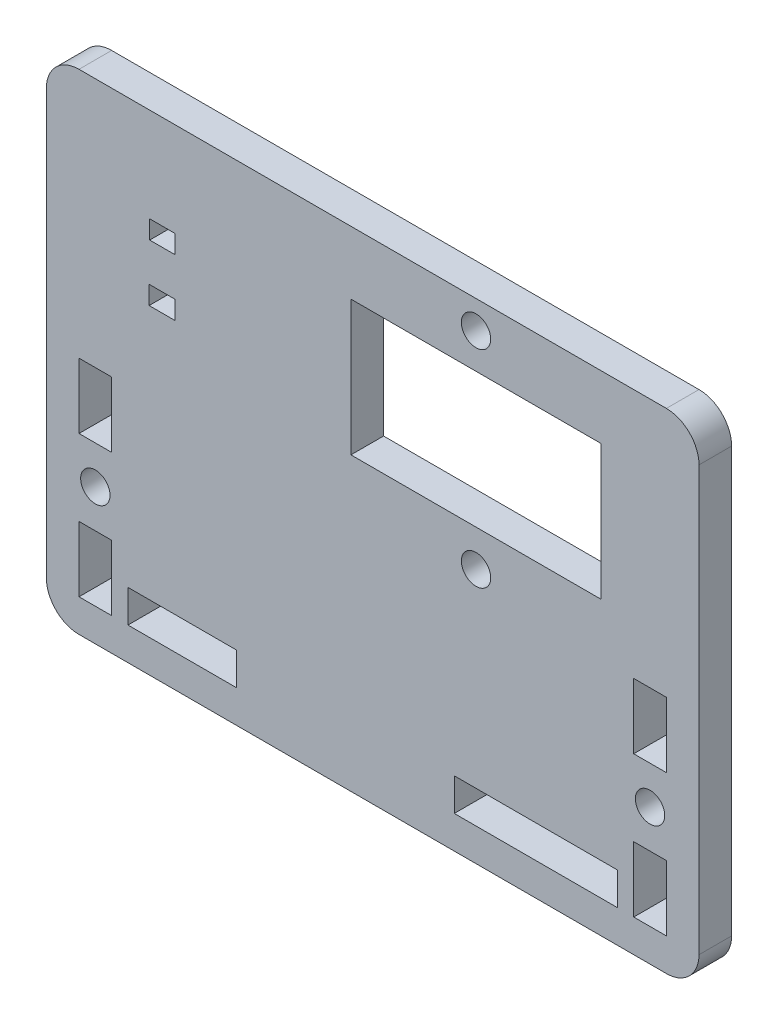
SolidWorks part; units mm, degrees
ref_plane "前视基准面" through (0, 0, 0) normal (0, 0, 1) x (1, 0, 0)
ref_plane "上视基准面" through (0, 0, 0) normal (0, 1, 0) x (1, 0, 0)
ref_plane "右视基准面" through (0, 0, 0) normal (1, 0, 0) x (0, 0, -1)
ref_plane "基准面1" through (0, 0, 0) normal (0, 0, -1) x (-1, 0, 0)
sketch "草图1" plane through (0, 0, 0) normal (0, 0, -1) x (-1, 0, 0)
  line L0 (-28.0668, 21.999) -> (-25.0668, 21.999)
  line L1 (-25.0668, 21.999) -> (-25.0668, 15.999)
  line L2 (-25.0668, 15.999) -> (-28.0668, 15.999)
  line L3 (-28.0668, 15.999) -> (-28.0668, 21.999)
  line L4 (-28.0668, 0) -> (25.9332, 0)
  line L5 (28.9332, 3) -> (28.9332, 41.999)
  line L6 (25.9332, 44.999) -> (-28.0668, 44.999)
  line L7 (-31.0668, 41.999) -> (-31.0668, 3)
  line L8 (-28.0668, 8.999) -> (-25.0668, 8.999)
  line L9 (-25.0668, 8.999) -> (-25.0668, 2.999)
  line L10 (-25.0668, 2.999) -> (-28.0668, 2.999)
  line L11 (-28.0668, 2.999) -> (-28.0668, 8.999)
  line L12 (-23.5678, 5.999) -> (-8.5678, 5.999)
  line L13 (-8.5678, 5.999) -> (-8.5678, 2.999)
  line L14 (-8.5678, 2.999) -> (-23.5678, 2.999)
  line L15 (-23.5678, 2.999) -> (-23.5678, 5.999)
  line L16 (-22.0668, 39.2) -> (0.9322, 39.2)
  line L17 (0.9322, 39.2) -> (0.9322, 26.799)
  line L18 (0.9322, 26.799) -> (-22.0668, 26.799)
  line L19 (-22.0668, 26.799) -> (-22.0668, 39.2)
  line L20 (17.1082, 36.343) -> (19.4352, 36.343)
  line L21 (19.4352, 36.343) -> (19.4352, 34.65)
  line L22 (19.4352, 34.65) -> (17.1082, 34.65)
  line L23 (17.1082, 34.65) -> (17.1082, 36.343)
  line L24 (17.1082, 31.104) -> (19.4892, 31.104)
  line L25 (19.4892, 31.104) -> (19.4892, 29.41)
  line L26 (19.4892, 29.41) -> (17.1082, 29.41)
  line L27 (17.1082, 29.41) -> (17.1082, 31.104)
  line L28 (22.9332, 21.999) -> (25.9332, 21.999)
  line L29 (25.9332, 21.999) -> (25.9332, 15.999)
  line L30 (25.9332, 15.999) -> (22.9332, 15.999)
  line L31 (22.9332, 15.999) -> (22.9332, 21.999)
  line L32 (22.9332, 8.999) -> (25.9332, 8.999)
  line L33 (25.9332, 8.999) -> (25.9332, 2.999)
  line L34 (25.9332, 2.999) -> (22.9332, 2.999)
  line L35 (22.9332, 2.999) -> (22.9332, 8.999)
  line L36 (11.4322, 5.999) -> (21.4322, 5.999)
  line L37 (21.4322, 5.999) -> (21.4322, 2.999)
  line L38 (21.4322, 2.999) -> (11.4322, 2.999)
  line L39 (11.4322, 2.999) -> (11.4322, 5.999)
  circle A0 centre (-10.5678, 42.429) radius 1.35
  circle A1 centre (24.4322, 12.499) radius 1.35
  circle A2 centre (-10.5678, 23.43) radius 1.35
  circle A3 centre (-26.5678, 12.499) radius 1.35
  arc A4 (25.9332, 0) -> (28.9332, 3) centre (25.9332, 3) ccw
  arc A5 (28.9332, 41.999) -> (25.9332, 44.999) centre (25.9332, 41.999) ccw
  arc A6 (-28.0668, 44.999) -> (-31.0668, 41.999) centre (-28.0668, 41.999) ccw
  arc A7 (-31.0668, 3) -> (-28.0668, 0) centre (-28.0668, 3) ccw
extrude "凸台-拉伸1" add sketch "草图1" against normal blind 3
